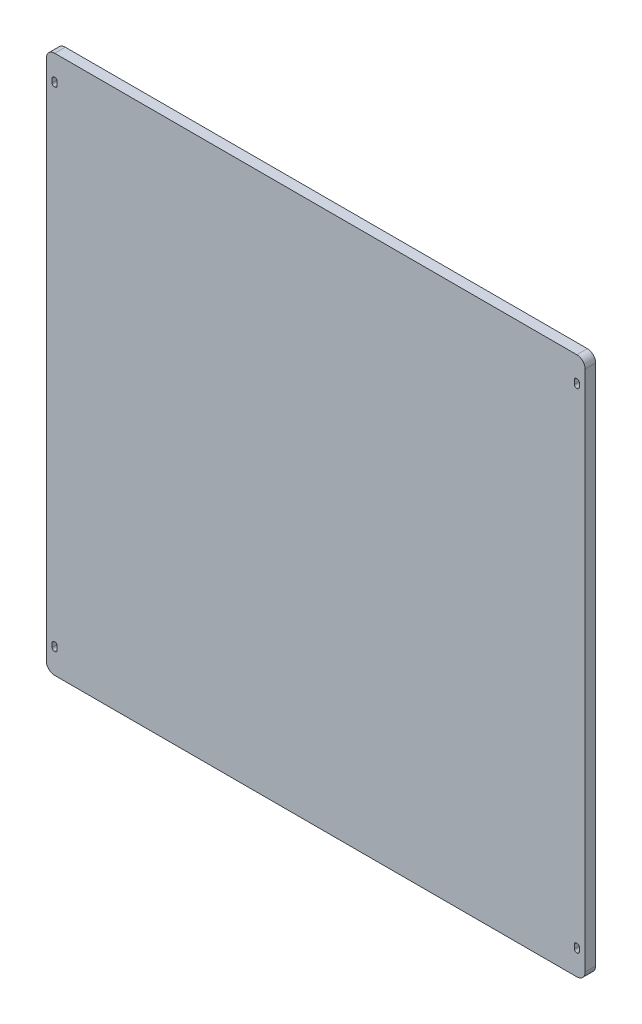
SolidWorks part; units mm, degrees
ref_plane "Front Plane" through (0, 0, 0) normal (0, 0, 1) x (1, 0, 0)
ref_plane "Top Plane" through (0, 0, 0) normal (0, 1, 0) x (1, 0, 0)
ref_plane "Right Plane" through (0, 0, 0) normal (1, 0, 0) x (0, 0, -1)
sketch "Sketch1" plane through (0, 0, 0) normal (0, 0, 1) x (1, 0, 0)
  line L0 (321.3203, -447.3706) -> (320.3203, -447.3706)
  line L1 (-316.8797, 175.3294) -> (330.8203, 175.3294)
  line L2 (-316.8797, 175.3294) -> (-316.8797, -472.3706)
  line L3 (-316.8797, -472.3706) -> (330.8203, -472.3706)
  line L4 (330.8203, 175.3294) -> (330.8203, -472.3706)
  line L5 (323.8203, -444.8706) -> (323.8203, -439.8706)
  line L6 (321.3203, -437.3706) -> (320.3203, -437.3706)
  line L7 (317.8203, -444.8706) -> (317.8203, -439.8706)
  line L8 (320.8203, -437.3706) -> (320.8203, -447.3706) construction
  line L9 (317.8203, -442.3706) -> (323.8203, -442.3706) construction
  line L10 (-306.3797, -447.3706) -> (-307.3797, -447.3706)
  line L11 (-309.8797, -444.8706) -> (-309.8797, -439.8706)
  line L12 (-306.3797, -437.3706) -> (-307.3797, -437.3706)
  line L13 (-303.8797, -444.8706) -> (-303.8797, -439.8706)
  line L14 (-306.3797, 140.3294) -> (-307.3797, 140.3294)
  line L15 (-309.8797, 142.8294) -> (-309.8797, 147.8294)
  line L16 (-306.3797, 150.3294) -> (-307.3797, 150.3294)
  line L17 (-303.8797, 142.8294) -> (-303.8797, 147.8294)
  line L18 (321.3203, 140.3294) -> (320.3203, 140.3294)
  line L19 (317.8203, 142.8294) -> (317.8203, 147.8294)
  line L20 (321.3203, 150.3294) -> (320.3203, 150.3294)
  line L21 (323.8203, 142.8294) -> (323.8203, 147.8294)
  arc A0 (321.3203, -447.3706) -> (323.8203, -444.8706) centre (321.3203, -444.8706) ccw
  arc A1 (323.8203, -439.8706) -> (321.3203, -437.3706) centre (321.3203, -439.8706) ccw
  arc A2 (320.3203, -447.3706) -> (317.8203, -444.8706) centre (320.3203, -444.8706) cw
  arc A3 (320.3203, -437.3706) -> (317.8203, -439.8706) centre (320.3203, -439.8706) ccw
  arc A4 (-307.3797, -447.3706) -> (-309.8797, -444.8706) centre (-307.3797, -444.8706) cw
  arc A5 (-307.3797, -437.3706) -> (-309.8797, -439.8706) centre (-307.3797, -439.8706) ccw
  arc A6 (-303.8797, -439.8706) -> (-306.3797, -437.3706) centre (-306.3797, -439.8706) ccw
  arc A7 (-306.3797, -447.3706) -> (-303.8797, -444.8706) centre (-306.3797, -444.8706) ccw
  arc A8 (-307.3797, 140.3294) -> (-309.8797, 142.8294) centre (-307.3797, 142.8294) cw
  arc A9 (-307.3797, 150.3294) -> (-309.8797, 147.8294) centre (-307.3797, 147.8294) ccw
  arc A10 (-303.8797, 147.8294) -> (-306.3797, 150.3294) centre (-306.3797, 147.8294) ccw
  arc A11 (-306.3797, 140.3294) -> (-303.8797, 142.8294) centre (-306.3797, 142.8294) ccw
  arc A12 (320.3203, 140.3294) -> (317.8203, 142.8294) centre (320.3203, 142.8294) cw
  arc A13 (320.3203, 150.3294) -> (317.8203, 147.8294) centre (320.3203, 147.8294) ccw
  arc A14 (323.8203, 147.8294) -> (321.3203, 150.3294) centre (321.3203, 147.8294) ccw
  arc A15 (321.3203, 140.3294) -> (323.8203, 142.8294) centre (321.3203, 142.8294) ccw
  point P21 (-309.8797, 145.3294)
  dimension "D2" = 2.5
  dimension "D1" = 647.7
  dimension "25.5in" = 647.7
  dimension "D3" = 6
  dimension "D4" = 10
  dimension "D5" = 175.3294
  dimension "D6" = 330.8203
  dimension "D7" = 30
  dimension "D8" = 2
  dimension "`" = 10
  dimension "D10" = 7
  dimension "D11" = 25
  dimension "D12" = 7
  dimension "D9" = 2
extrude "Boss-Extrude1" add sketch "Sketch1" along normal blind 12.7 contours L2 L3 L4 L1 | L14 A8 L15 A9 L16 A10 L17 A11 | L18 A12 L19 A13 L20 A14 L21 A15 | L0 A2 L7 A3 L6 A1 L5 A0 | L10 A4 L11 A5 L12 A6 L13 A7
fillet "Fillet1" radius 10 4 edges at (330.8203, -472.3706, 6.35) (-316.8797, -472.3706, 6.35) (-316.8797, 175.3294, 6.35) (330.8203, 175.3294, 6.35)
